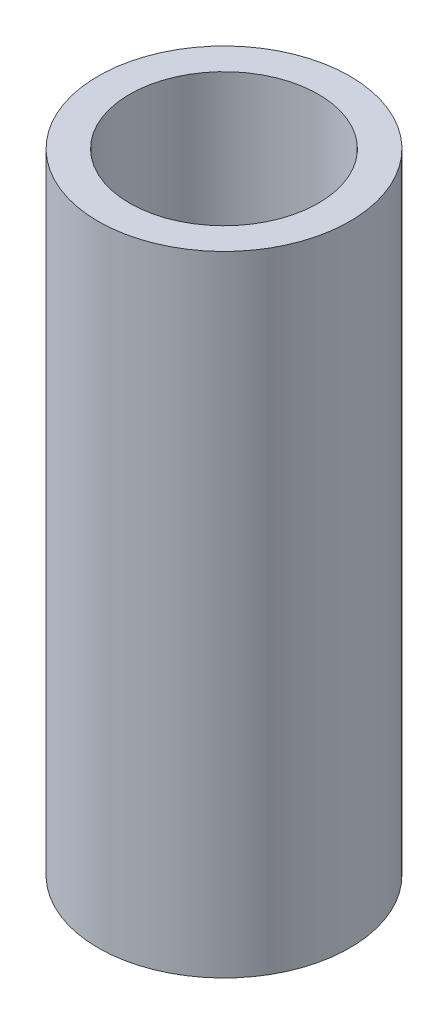
SolidWorks part; units mm, degrees
ref_plane "Front Plane" through (0, 0, 0) normal (0, 0, 1) x (1, 0, 0)
ref_plane "Top Plane" through (0, 0, 0) normal (0, 1, 0) x (1, 0, 0)
ref_plane "Right Plane" through (0, 0, 0) normal (1, 0, 0) x (0, 0, -1)
sketch "Sketch1" plane through (0, 0, 0) normal (0, 1, 0) x (1, 0, 0)
  circle A0 centre (0, 0) radius 4
  circle A1 centre (0, 0) radius 3
  dimension "D1" = 6
  dimension "D2" = 8
extrude "Boss-Extrude1" add sketch "Sketch1" along normal mid plane 20
